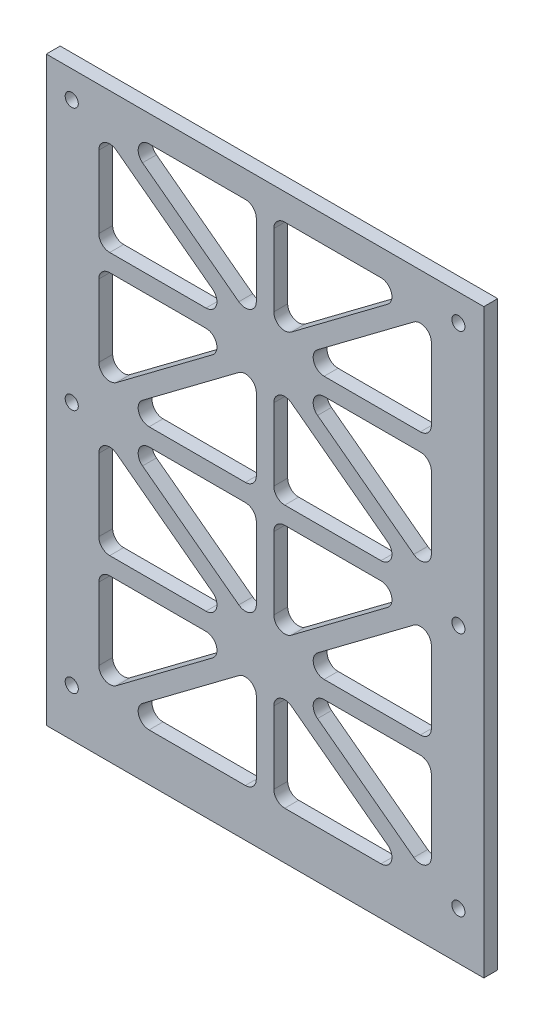
SolidWorks part; units mm, degrees
ref_plane "Front Plane" through (0, 0, 0) normal (0, 0, 1) x (1, 0, 0)
ref_plane "Top Plane" through (0, 0, 0) normal (0, 1, 0) x (1, 0, 0)
ref_plane "Right Plane" through (0, 0, 0) normal (1, 0, 0) x (0, 0, -1)
sketch "Sketch1" plane through (0, 0, 0) normal (0, 0, 1) x (1, 0, 0)
  line L0 (0, -116.2131) -> (0, -56.2131) construction
  line L1 (4, 119.7869) -> (4, 71.7869)
  line L2 (68, 119.7869) -> (4, 71.7869)
  line L3 (0, -116.2131) -> (80, -116.2131) construction
  line L4 (80, -116.2131) -> (80, -56.2131) construction
  line L5 (0, 131.8479) -> (0, -133.9191)
  line L6 (0, -133.9191) -> (100, -133.9191)
  line L7 (0, -56.2131) -> (80, -116.2131) construction
  line L8 (0, -56.2131) -> (80, -56.2131) construction
  line L9 (80, -56.2131) -> (80, 3.7869) construction
  line L10 (80, 3.7869) -> (0, -56.2131) construction
  line L11 (0, -56.2131) -> (0, 3.7869) construction
  line L12 (0, 3.7869) -> (80, 3.7869) construction
  line L13 (80, 3.7869) -> (0, 63.7869) construction
  line L14 (0, 63.7869) -> (0, 3.7869) construction
  line L15 (0, 63.7869) -> (80, 63.7869) construction
  line L16 (80, 63.7869) -> (80, 3.7869) construction
  line L17 (80, 63.7869) -> (80, 123.7869) construction
  line L18 (80, 123.7869) -> (0, 63.7869) construction
  line L19 (0, 123.7869) -> (80, 123.7869) construction
  line L20 (0, 123.7869) -> (0, 63.7869) construction
  line L21 (4, 119.7869) -> (68, 119.7869)
  line L22 (76, 115.7869) -> (12, 67.7869)
  line L23 (12, 67.7869) -> (76, 67.7869)
  line L24 (76, 67.7869) -> (76, 115.7869)
  line L25 (12, 59.7869) -> (76, 59.7869)
  line L26 (76, 59.7869) -> (76, 11.7869)
  line L27 (76, 11.7869) -> (12, 59.7869)
  line L28 (68, 7.7869) -> (4, 55.7869)
  line L29 (4, 55.7869) -> (4, 7.7869)
  line L30 (4, 7.7869) -> (68, 7.7869)
  line L31 (4, -0.2131) -> (68, -0.2131)
  line L32 (68, -0.2131) -> (4, -48.2131)
  line L33 (4, -48.2131) -> (4, -0.2131)
  line L34 (76, -4.2131) -> (12, -52.2131)
  line L35 (12, -52.2131) -> (76, -52.2131)
  line L36 (76, -52.2131) -> (76, -4.2131)
  line L37 (12, -60.2131) -> (76, -60.2131)
  line L38 (76, -108.2131) -> (76, -60.2131)
  line L39 (12, -60.2131) -> (76, -108.2131)
  line L40 (4, -112.2131) -> (4, -64.2131)
  line L41 (4, -64.2131) -> (68, -112.2131)
  line L42 (4, -112.2131) -> (68, -112.2131)
  line L43 (100, -133.9191) -> (100, 131.8479)
  line L44 (100, 131.8479) -> (0, 131.8479)
  circle A2 centre (88.3661, 119.5311) radius 3
  circle A3 centre (88.3661, -0.2131) radius 3
  circle A4 centre (88.3661, -112.2131) radius 3
  point P0 (0, 0)
  point P15 (89.2809, -0.2131)
  point P41 (0, 0)
  point P42 (85.8483, 119.5311)
  point P43 (88.3661, 119.5311)
  point P50 (0, 0)
  point P51 (89.9726, 119.7869)
  point P52 (0, 0)
  point P53 (0, 0)
  dimension "D12" = 6
  dimension "D2" = 240
  dimension "D11" = 80
  dimension "D13" = 100
  dimension "D3" = 4
  dimension "D4" = 4
  dimension "D5" = 4
  dimension "D6" = 4
  dimension "D7" = 4
  dimension "D8" = 4
  dimension "D9" = 4
  dimension "D10" = 4
extrude "Boss-Extrude2" add sketch "Sketch1" along normal blind 6.35
fillet "Cutout_Fillets" radius 5 24 edges at (4, 71.7869, 3.175) (68, 119.7869, 3.175) (4, 119.7869, 3.175) (12, 67.7869, 3.175) (76, 67.7869, 3.175) (76, 115.7869, 3.175) (76, 11.7869, 3.175) (76, 59.7869, 3.175) (12, 59.7869, 3.175) (4, 7.7869, 3.175) (4, 55.7869, 3.175) (68, 7.7869, 3.175) (68, -0.2131, 3.175) (4, -0.2131, 3.175) (4, -48.2131, 3.175) (76, -52.2131, 3.175) (76, -4.2131, 3.175) (12, -52.2131, 3.175) (12, -60.2131, 3.175) (76, -60.2131, 3.175) (76, -108.2131, 3.175) (68, -112.2131, 3.175) (4, -112.2131, 3.175) (4, -64.2131, 3.175)
mirror "Mirror2" about plane through (0, 131.8479, 6.35) normal (1, 0, 0) of "Cutout_Fillets", "Boss-Extrude2"
